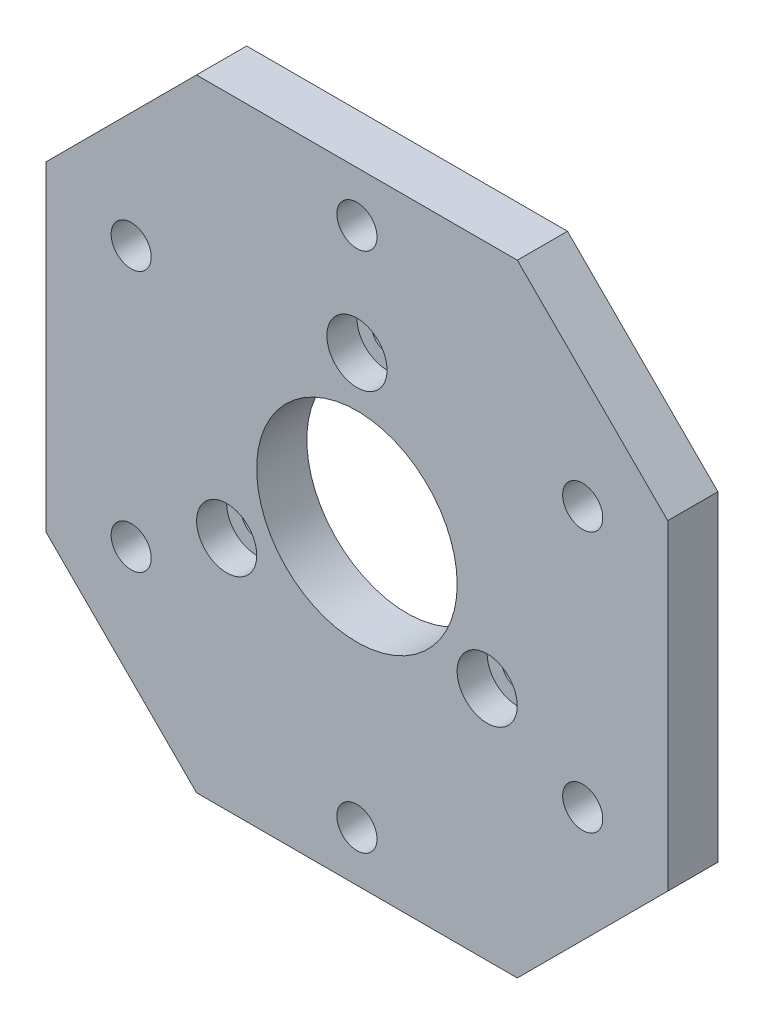
SolidWorks part; units mm, degrees
ref_plane "Front Plane" through (0, 0, 0) normal (0, 0, 1) x (1, 0, 0)
ref_plane "Top Plane" through (0, 0, 0) normal (0, 1, 0) x (1, 0, 0)
ref_plane "Right Plane" through (0, 0, 0) normal (1, 0, 0) x (0, 0, -1)
sketch "Sketch1" plane through (0, 0, 0) normal (0, 0, 1) x (1, 0, 0)
  line L0 (0, 0) -> (0, 26) construction
  line L1 (-31, -31) -> (31, -31)
  line L2 (-31, -31) -> (-31, 31)
  line L3 (-31, 31) -> (31, 31)
  line L4 (31, -31) -> (31, 31)
  line L5 (-31, -31) -> (31, 31) construction
  line L6 (-31, 31) -> (31, -31) construction
  line L7 (-31, 0) -> (31, 0) construction
  circle A0 centre (0, 0) radius 10
  circle A1 centre (0, 26) radius 2
  circle A7 centre (0, 15) radius 1.5
  circle A12 centre (22.5167, 13) radius 2
  circle A13 centre (22.5167, -13) radius 2
  circle A14 centre (0, -26) radius 2
  circle A15 centre (-22.5167, -13) radius 2
  circle A16 centre (-22.5167, 13) radius 2
  circle A17 centre (12.9904, -7.5) radius 1.5
  circle A18 centre (-12.9904, -7.5) radius 1.5
  point P0 (0, 0)
  point P21 (0, 0)
  point P22 (-3.4641, 2)
  point P26 (-5.1962, 3)
  point P30 (0, 0)
  point P34 (0, 0)
  dimension "D2" = 20
  dimension "D4" = 4
  dimension "D5" = 6
  dimension "D6" = 3
  dimension "D7" = 15
  dimension "D8" = 3
  dimension "D1" = 62
  dimension "D3" = 26
extrude "Boss-Extrude1" add sketch "Sketch1" along normal blind 5
sketch "Sketch3" plane through (0, 0, 0) normal (0, 0, -1) x (-1, 0, 0)
  line L0 (-31, 31) -> (-31, 16)
  line L1 (-31, -31) -> (-31, 31) construction
  line L2 (-31, 31) -> (-16, 31)
  line L3 (-31, 31) -> (31, 31) construction
  line L4 (-16, 31) -> (-31, 16)
  line L5 (0, 31) -> (0, -31) construction
  line L6 (31, -31) -> (-31, -31) construction
  line L7 (-31, 0) -> (31, 0) construction
  line L8 (31, 31) -> (31, -31) construction
  line L9 (31, 31) -> (16, 31)
  line L10 (31, 31) -> (31, 16)
  line L11 (16, 31) -> (31, 16)
  line L12 (31, -31) -> (31, -16)
  line L13 (16, -31) -> (31, -16)
  line L14 (31, -31) -> (16, -31)
  line L15 (-31, -31) -> (-16, -31)
  line L16 (-31, -31) -> (-31, -16)
  line L17 (-16, -31) -> (-31, -16)
  dimension "D1" = 15
  dimension "D2" = 15
extrude "Cut-Extrude2" cut sketch "Sketch3" against normal blind 10
sketch "Sketch4" plane through (0, 0, 5) normal (0, 0, 1) x (1, 0, 0)
  circle A0 centre (0, 15) radius 3
  circle A1 centre (12.9904, -7.5) radius 3
  circle A2 centre (-12.9904, -7.5) radius 3
  dimension "D1" = 6
  dimension "D2" = 6
  dimension "D3" = 6
extrude "Cut-Extrude3" cut sketch "Sketch4" against normal blind 3
